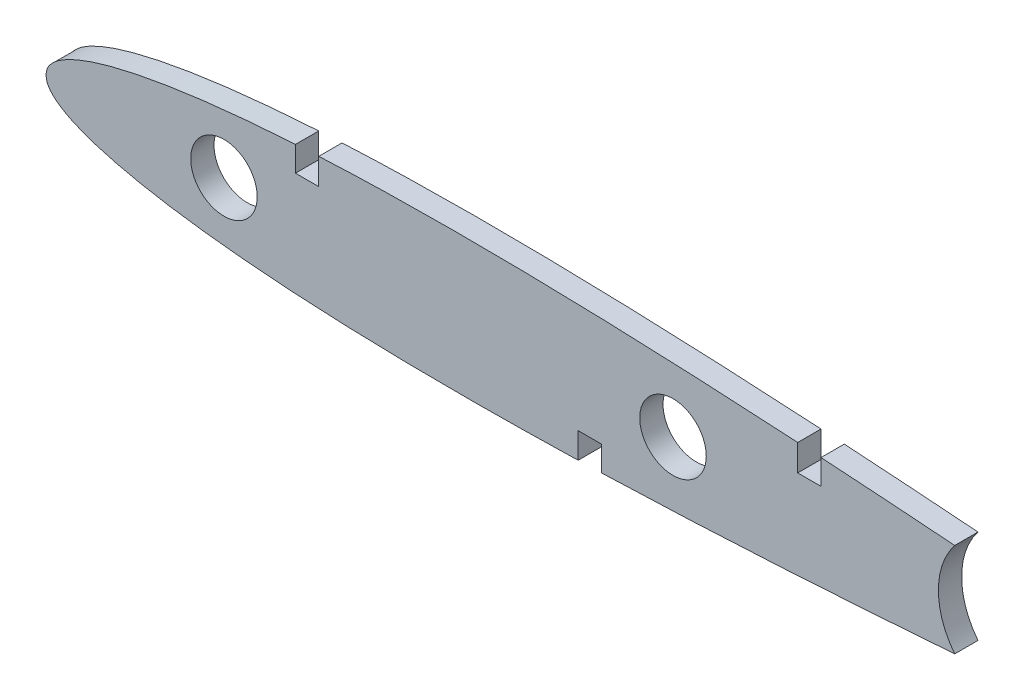
SolidWorks part; units mm, degrees
material "Фанера"
ref_plane "Спереди" through (0, 0, 0) normal (0, 0, 1) x (1, 0, 0)
ref_plane "Сверху" through (0, 0, 0) normal (0, 1, 0) x (1, 0, 0)
ref_plane "Справа" through (0, 0, 0) normal (1, 0, 0) x (0, 0, -1)
curve "Кривая1"
  spline degree 3 poles (200, 0.1747, 0) (199.6007, 0.2213, 0) (198.4854, 0.3514, 0) (196.462, 0.5838, 0) (193.7856, 0.8861, 0) (190.6579, 1.2319, 0) (187.1764, 1.6078, 0) (183.4067, 2.0045, 0) (179.3984, 2.4149, 0) (175.1909, 2.8335, 0) (170.8176, 3.2558, 0) (166.3067, 3.6778, 0) (161.6831, 4.0963, 0) (156.9692, 4.5083, 0) (152.1848, 4.9111, 0) (147.3484, 5.3022, 0) (142.4768, 5.6794, 0) (137.5855, 6.0402, 0) (132.6892, 6.3824, 0) (127.8016, 6.7038, 0) (122.9356, 7.0023, 0) (118.1034, 7.2757, 0) (113.3167, 7.5219, 0) (108.5864, 7.7388, 0) (103.9232, 7.9245, 0) (99.3373, 8.0772, 0) (94.8383, 8.1952, 0) (90.4357, 8.2769, 0) (86.1385, 8.321, 0) (81.9555, 8.3264, 0) (77.8951, 8.2921, 0) (73.9656, 8.2177, 0) (70.1749, 8.1027, 0) (66.5308, 7.947, 0) (63.0408, 7.751, 0) (59.7122, 7.515, 0) (56.5522, 7.2398, 0) (53.5677, 6.9266, 0) (50.7656, 6.5764, 0) (48.1524, 6.1907, 0) (45.7346, 5.7713, 0) (43.5185, 5.3197, 0) (41.5102, 4.8379, 0) (39.7154, 4.3278, 0) (38.1397, 3.791, 0) (36.7878, 3.2294, 0) (35.6652, 2.6441, 0) (34.771, 2.0345, 0) (34.119, 1.3968, 0) (33.6837, 0.7187, 0) (33.627, 0.2317, 0) (33.6, 0, 0) knots 0 0 0 0 0.007145 0.019956 0.036196 0.055011 0.075879 0.098429 0.122376 0.147488 0.173572 0.20046 0.228005 0.256076 0.284555 0.313333 0.34231 0.371393 0.400496 0.429538 0.458442 0.487136 0.515552 0.543624 0.57129 0.598491 0.62517 0.651272 0.676746 0.701542 0.725611 0.748908 0.771388 0.793008 0.813728 0.833508 0.85231 0.870097 0.886836 0.902493 0.917037 0.930441 0.94268 0.953734 0.96359 0.972247 0.979722 0.986065 0.991385 0.995901 1 1 1 1
curve "Кривая2"
  spline degree 3 poles (33.6, 0, 0) (33.627, -0.2317, 0) (33.6837, -0.7187, 0) (34.119, -1.3968, 0) (34.771, -2.0345, 0) (35.6652, -2.6441, 0) (36.7878, -3.2294, 0) (38.1397, -3.791, 0) (39.7154, -4.3278, 0) (41.5102, -4.8379, 0) (43.5185, -5.3197, 0) (45.7346, -5.7713, 0) (48.1524, -6.1907, 0) (50.7656, -6.5764, 0) (53.5677, -6.9266, 0) (56.5522, -7.2398, 0) (59.7122, -7.515, 0) (63.0408, -7.751, 0) (66.5308, -7.947, 0) (70.1749, -8.1027, 0) (73.9656, -8.2177, 0) (77.8951, -8.2921, 0) (81.9555, -8.3264, 0) (86.1385, -8.321, 0) (90.4357, -8.2769, 0) (94.8383, -8.1952, 0) (99.3373, -8.0772, 0) (103.9232, -7.9245, 0) (108.5864, -7.7388, 0) (113.3167, -7.5219, 0) (118.1034, -7.2757, 0) (122.9356, -7.0023, 0) (127.8016, -6.7038, 0) (132.6892, -6.3824, 0) (137.5855, -6.0402, 0) (142.4768, -5.6794, 0) (147.3484, -5.3022, 0) (152.1848, -4.9111, 0) (156.9692, -4.5083, 0) (161.6831, -4.0963, 0) (166.3067, -3.6778, 0) (170.8176, -3.2558, 0) (175.1909, -2.8335, 0) (179.3984, -2.4149, 0) (183.4067, -2.0045, 0) (187.1764, -1.6078, 0) (190.6579, -1.2319, 0) (193.7856, -0.8861, 0) (196.462, -0.5838, 0) (198.4854, -0.3514, 0) (199.6007, -0.2213, 0) (200, -0.1747, 0) knots 0 0 0 0 0.004099 0.008615 0.013935 0.020278 0.027753 0.03641 0.046266 0.05732 0.069559 0.082963 0.097507 0.113164 0.129903 0.14769 0.166492 0.186272 0.206992 0.228612 0.251092 0.274389 0.298458 0.323254 0.348728 0.37483 0.401509 0.42871 0.456376 0.484448 0.512864 0.541558 0.570462 0.599504 0.628607 0.65769 0.686667 0.715445 0.743924 0.771995 0.79954 0.826428 0.852512 0.877624 0.901571 0.924121 0.944989 0.963804 0.980044 0.992855 1 1 1 1
sketch "Эскиз1" plane through (0, 0, 0) normal (0, 0, 1) x (1, 0, 0)
  line L0 (200, 0.1747) -> (200, -0.1747)
  line L1 (97.6, -8.1212) -> (97.6, -5.0393)
  line L2 (97.6, -5.0393) -> (100.4, -5.0393)
  line L3 (100.4, -5.0393) -> (100.4, -8.0393)
  line L4 (124, 6.9352) -> (124, 3.7634)
  line L5 (124, 3.7634) -> (126.8, 3.7634)
  line L6 (126.8, 3.7634) -> (126.8, 6.7634)
  line L7 (63.6, 7.7774) -> (63.6, 4.7774)
  line L8 (63.6, 4.7774) -> (66.4, 4.7774)
  line L9 (66.4, 4.7774) -> (66.4, 7.9325)
  circle A0 centre (109, 0) radius 4
  circle A1 centre (55, 0) radius 4
  arc A2 (150, 5.0871) -> (150, -5.0871) centre (150, 0) ccw
  arc A3 (142.8797, 5.6459) -> (142.8797, -5.6459) centre (150, 0) ccw
  circle A5 centre (150, 0) radius 1.5
  spline S0 degree 3 poles (-6642.5284, -2091.6587) (159.7007, 64.8565) (27.0549, 9.6093) (34.119, -1.3968) (34.771, -2.0345) (35.6652, -2.6441) (36.7878, -3.2294) (38.1397, -3.791) (39.7154, -4.3278) (41.5102, -4.8379) (43.5185, -5.3197) (45.7346, -5.7713) (48.1524, -6.1907) (50.7656, -6.5764) (53.5677, -6.9266) (56.5522, -7.2398) (59.7122, -7.515) (63.0408, -7.751) (66.5308, -7.947) (70.1749, -8.1027) (73.9656, -8.2177) (77.8951, -8.2921) (81.9555, -8.3264) (86.1385, -8.321) (90.4357, -8.2769) (94.8383, -8.1952) (99.3373, -8.0772) (103.9232, -7.9245) (108.5864, -7.7388) (113.3167, -7.5219) (118.1034, -7.2757) (122.9356, -7.0023) (127.8016, -6.7038) (132.6892, -6.3824) (137.5855, -6.0402) (142.4768, -5.6794) (147.3484, -5.3022) (152.1848, -4.9111) (156.9692, -4.5083) (161.6831, -4.0963) (167.7684, -3.5455) (173.6854, -2.9833) (179.3984, -2.4149) (183.4067, -2.0045) (187.1764, -1.6078) (190.6579, -1.2319) (193.7856, -0.8861) (196.462, -0.5838) (320.1247, 13.6227) (440.1879, 50.9049) (1369.7937, -6889.545) knots -0.212218 -0.212218 -0.212218 -0.212218 0.004099 0.008615 0.013935 0.020278 0.027753 0.03641 0.046266 0.05732 0.069559 0.082963 0.097507 0.113164 0.129903 0.14769 0.166492 0.186272 0.206992 0.228612 0.251092 0.274389 0.298458 0.323254 0.348728 0.37483 0.401509 0.42871 0.456376 0.484448 0.512864 0.541558 0.570462 0.599504 0.628607 0.65769 0.686667 0.715445 0.743924 0.771995 0.79954 0.852512 0.877624 0.901571 0.924121 0.944989 0.963804 0.980044 0.992855 3.175981 3.175981 3.175981 3.175981 only from (33.6, 0) to (200, -0.1747) construction
  spline S1 degree 3 poles (1761.9285, 9863.4167) (470.2616, -60.6211) (335.5203, -15.3913) (196.462, 0.5838) (193.7856, 0.8861) (190.6579, 1.2319) (187.1764, 1.6078) (183.4067, 2.0045) (179.3984, 2.4149) (173.6854, 2.9833) (167.7684, 3.5455) (161.6831, 4.0963) (156.9692, 4.5083) (152.1848, 4.9111) (147.3484, 5.3022) (142.4768, 5.6794) (137.5855, 6.0402) (132.6892, 6.3824) (127.8016, 6.7038) (122.9356, 7.0023) (118.1034, 7.2757) (113.3167, 7.5219) (108.5864, 7.7388) (103.9232, 7.9245) (99.3373, 8.0772) (94.8383, 8.1952) (90.4357, 8.2769) (86.1385, 8.321) (81.9555, 8.3264) (77.8951, 8.2921) (73.9656, 8.2177) (70.1749, 8.1027) (66.5308, 7.947) (63.0408, 7.751) (59.7122, 7.515) (56.5522, 7.2398) (53.5677, 6.9266) (50.7656, 6.5764) (48.1524, 6.1907) (45.7346, 5.7713) (43.5185, 5.3197) (41.5102, 4.8379) (39.7154, 4.3278) (38.1397, 3.791) (36.7878, 3.2294) (35.6652, 2.6441) (34.771, 2.0345) (34.119, 1.3968) (26.2193, -10.9112) (193.8843, -78.8941) (-9497.4814, 2997.3842) knots -2.451389 -2.451389 -2.451389 -2.451389 0.007145 0.019956 0.036196 0.055011 0.075879 0.098429 0.122376 0.147488 0.20046 0.228005 0.256076 0.284555 0.313333 0.34231 0.371393 0.400496 0.429538 0.458442 0.487136 0.515552 0.543624 0.57129 0.598491 0.62517 0.651272 0.676746 0.701542 0.725611 0.748908 0.771388 0.793008 0.813728 0.833508 0.85231 0.870097 0.886836 0.902493 0.917037 0.930441 0.94268 0.953734 0.96359 0.972247 0.979722 0.986065 0.991385 0.995901 1.238969 1.238969 1.238969 1.238969 only from (200, 0.1747) to (33.6, 0) construction
  spline S2 degree 3 poles (33.6, 0) (33.627, -0.2317) (33.6837, -0.7187) (34.119, -1.3968) (34.771, -2.0345) (35.6652, -2.6441) (36.7878, -3.2294) (38.1397, -3.791) (39.7154, -4.3278) (41.5102, -4.8379) (43.5185, -5.3197) (45.7346, -5.7713) (48.1524, -6.1907) (50.7656, -6.5764) (53.5677, -6.9266) (56.5522, -7.2398) (59.7122, -7.515) (63.0408, -7.751) (66.5308, -7.947) (70.1749, -8.1027) (73.9656, -8.2177) (77.8951, -8.2921) (81.9555, -8.3264) (86.1385, -8.321) (90.4357, -8.2769) (94.2689, -8.2058) (96.6686, -8.1464) (97.6, -8.1212) knots 0 0 0 0 0.004099 0.008615 0.013935 0.020278 0.027753 0.03641 0.046266 0.05732 0.069559 0.082963 0.097507 0.113164 0.129903 0.14769 0.166492 0.186272 0.206992 0.228612 0.251092 0.274389 0.298458 0.323254 0.348728 0.37483 0.391389 0.391389 0.391389 0.391389
  spline S3 degree 3 poles (200, 0.1747) (199.6007, 0.2213) (198.4854, 0.3514) (196.462, 0.5838) (193.7856, 0.8861) (190.6579, 1.2319) (187.1764, 1.6078) (183.4067, 2.0045) (179.3984, 2.4149) (173.6854, 2.9833) (167.7684, 3.5455) (161.6831, 4.0963) (156.9692, 4.5083) (152.1848, 4.9111) (147.3484, 5.3022) (142.4768, 5.6794) (137.5855, 6.0402) (132.6892, 6.3824) (129.0934, 6.6189) (127.1312, 6.7427) (126.8, 6.7634) knots 0 0 0 0 0.007145 0.019956 0.036196 0.055011 0.075879 0.098429 0.122376 0.147488 0.20046 0.228005 0.256076 0.284555 0.313333 0.34231 0.371393 0.400496 0.429538 0.435436 0.435436 0.435436 0.435436
  spline S4 degree 3 poles (124, 6.9352) (123.6412, 6.9567) (121.6707, 7.0739) (118.1034, 7.2757) (113.3167, 7.5219) (108.5864, 7.7388) (103.9232, 7.9245) (99.3373, 8.0772) (94.8383, 8.1952) (90.4357, 8.2769) (86.1385, 8.321) (81.9555, 8.3264) (77.8951, 8.2921) (73.9656, 8.2177) (70.1749, 8.1027) (67.6688, 7.9956) (66.4269, 7.9339) (66.4, 7.9325) knots 0.452054 0.452054 0.452054 0.452054 0.458442 0.487136 0.515552 0.543624 0.57129 0.598491 0.62517 0.651272 0.676746 0.701542 0.725611 0.748908 0.771388 0.793008 0.793486 0.793486 0.793486 0.793486
  spline S5 degree 3 poles (100.4, -8.0393) (101.5657, -8.0027) (104.2872, -7.91) (108.5864, -7.7388) (113.3167, -7.5219) (118.1034, -7.2757) (122.9356, -7.0023) (127.8016, -6.7038) (132.6892, -6.3824) (137.5855, -6.0402) (142.4768, -5.6794) (147.3484, -5.3022) (152.1848, -4.9111) (156.9692, -4.5083) (161.6831, -4.0963) (167.7684, -3.5455) (173.6854, -2.9833) (179.3984, -2.4149) (183.4067, -2.0045) (187.1764, -1.6078) (190.6579, -1.2319) (193.7856, -0.8861) (196.462, -0.5838) (198.4854, -0.3514) (199.6007, -0.2213) (200, -0.1747) knots 0.407983 0.407983 0.407983 0.407983 0.42871 0.456376 0.484448 0.512864 0.541558 0.570462 0.599504 0.628607 0.65769 0.686667 0.715445 0.743924 0.771995 0.79954 0.852512 0.877624 0.901571 0.924121 0.944989 0.963804 0.980044 0.992855 1 1 1 1
  spline S6 degree 3 poles (63.6, 7.7774) (63.3962, 7.765) (62.0815, 7.683) (59.7122, 7.515) (56.5522, 7.2398) (53.5677, 6.9266) (50.7656, 6.5764) (48.1524, 6.1907) (45.7346, 5.7713) (43.5185, 5.3197) (41.5102, 4.8379) (39.7154, 4.3278) (38.1397, 3.791) (36.7878, 3.2294) (35.6652, 2.6441) (34.771, 2.0345) (34.119, 1.3968) (33.6837, 0.7187) (33.627, 0.2317) (33.6, 0) knots 0.810099 0.810099 0.810099 0.810099 0.813728 0.833508 0.85231 0.870097 0.886836 0.902493 0.917037 0.930441 0.94268 0.953734 0.96359 0.972247 0.979722 0.986065 0.991385 0.995901 1 1 1 1
  point P14 (99, -5.0393)
  point P20 (65, 4.7774)
  dimension "D1" = 8
  dimension "D2" = 8
  dimension "D16" = 5.0871
  dimension "D17" = 9.0871
  dimension "D18" = 3
  dimension "D3" = 75.4
  dimension "D4" = 21.4
  dimension "D5" = 2.8
  dimension "D6" = 2.8
  dimension "D7" = 10
  dimension "D8" = 15
  dimension "D9" = 3
  dimension "D10" = 3
  dimension "D11" = 2.8
  dimension "D12" = 10
  dimension "D13" = 3
  dimension "D14" = 116.4
  dimension "D15" = 10.1742
extrude "Бобышка-Вытянуть1" add sketch "Эскиз1" along normal mid plane 2.8 contours L7 S6 S2 L1 L2 L3 S5 A3 S3 L6 L5 L4 S4 L9 L8 A0 A1
equation "\"D3@Эскиз1\"=109-33.6"
equation "\"D16@Эскиз1\"=\"D15@Эскиз1\"/2"
equation "\"D17@Эскиз1\"=\"D16@Эскиз1\"+4"
